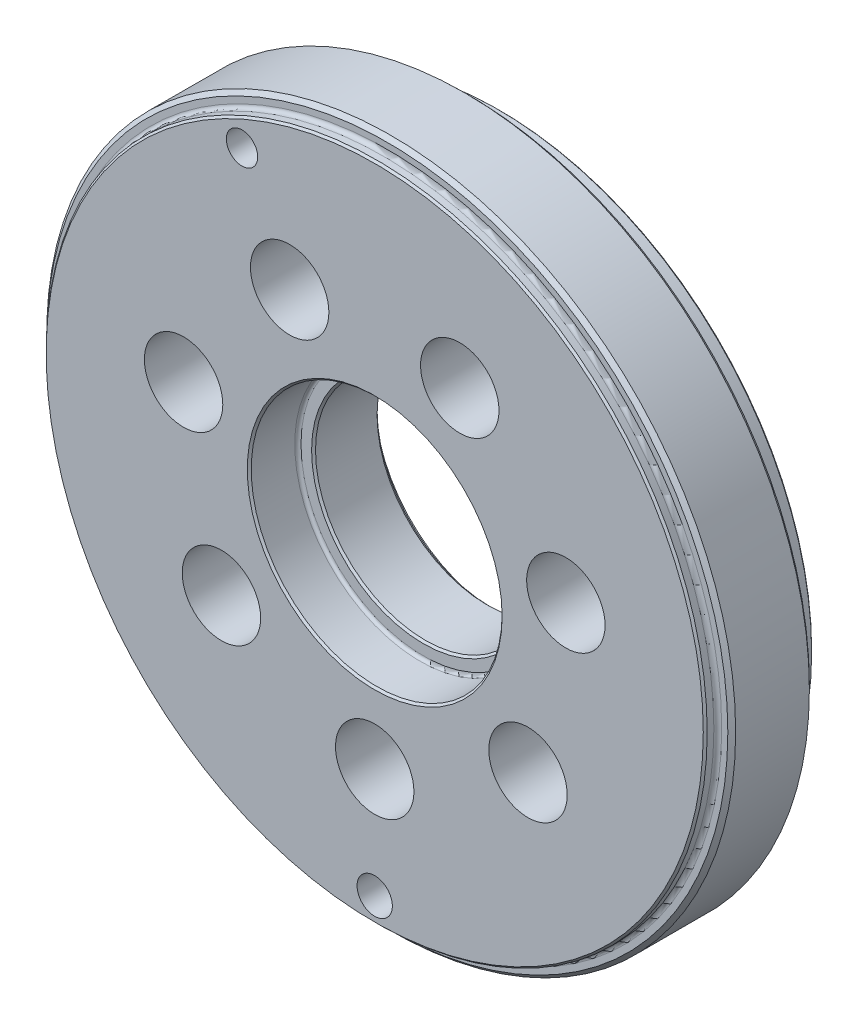
SolidWorks part; units mm, degrees
material "2P Cast Iron"
ref_plane "Front Plane" through (0, 0, 0) normal (0, 0, 1) x (1, 0, 0)
ref_plane "Top Plane" through (0, 0, 0) normal (0, 1, 0) x (1, 0, 0)
ref_plane "Right Plane" through (0, 0, 0) normal (1, 0, 0) x (0, 0, -1)
sketch "Sketch1" plane through (0, 0, 0) normal (0, 0, 1) x (1, 0, 0)
  line L0 (0, 0) -> (86.0326, 0) construction
  line L1 (0, 0) -> (0, 58.9688) construction
  circle A4 centre (0, 0) radius 14
  circle A5 centre (0, 0) radius 43.93
  dimension "D6" = 28
  dimension "D7" = 87.86
extrude "Extrude1" add sketch "Sketch1" against normal blind 16
sketch "Sketch13" plane through (0, 0, 0) normal (1, 0, 0) x (0, 0, -1)
  line L0 (0, 0) -> (24.7077, 0) construction
  line L1 (5.8, 16) -> (0.25, 16)
  line L2 (16, -43.93) -> (16, 43.93) construction
  line L3 (6.2, 15.6) -> (6.2, 14.25)
  line L4 (6.45, 14) -> (14.3, 14)
  line L5 (14.8, 14.5) -> (14.8, 15.6)
  line L6 (15.2, 16) -> (16, 16)
  line L7 (16, 39.72) -> (15.75, 39.97)
  line L9 (0.25, 16) -> (0, 16.25)
  line L10 (14.3, 14) -> (14.8, 14.5)
  line L11 (6.2, 14.25) -> (6.45, 14)
  line L12 (0, 41.9) -> (0.25, 42.15)
  line L13 (0, 43.93) -> (0, -43.93) construction
  line L14 (0, 16.25) -> (0, 41.9)
  line L15 (0.25, 42.15) -> (1.1, 42.15)
  line L16 (1.6, 42.65) -> (1.6, 50.0474)
  line L17 (1.6, 50.0474) -> (-4.8431, 50.0474)
  line L18 (0, 0) -> (19.0487, 0)
  line L19 (16, 16) -> (16, 39.72)
  line L20 (15.75, 39.97) -> (12.4, 39.97)
  line L21 (12, 40.37) -> (12, 50.0474)
  line L22 (12, 50.0474) -> (19.0487, 50.0474)
  line L23 (19.0487, 50.0474) -> (19.0487, 0)
  line L24 (-4.8431, 50.0474) -> (-4.8431, 0)
  line L25 (0, 0) -> (-4.8431, 0)
  arc A0 (5.8, 16) -> (6.2, 15.6) centre (5.8, 15.6) cw
  arc A1 (14.8, 15.6) -> (15.2, 16) centre (15.2, 15.6) cw
  arc A3 (1.1, 42.15) -> (1.6, 42.65) centre (1.1, 42.65) ccw
  arc A4 (12.4, 39.97) -> (12, 40.37) centre (12.4, 40.37) cw
  point P24 (0, 42.15)
  point P39 (16, 39.97)
  dimension "D6" = 0.4
  dimension "D14" = 0.25
  dimension "D18" = 0.4
  dimension "D20" = 0.5
  dimension "D1" = 32
  dimension "D2" = 32
  dimension "D3" = 100.0949
  dimension "D4" = 28
  dimension "D7" = 0.25
  dimension "D8" = 45
  dimension "D9" = 45
  dimension "D10" = 0.5
  dimension "D11" = 1.2
  dimension "D12" = 10.4
  dimension "D13" = 45
  dimension "D15" = 79.94
  dimension "D16" = 84.3
  dimension "D17" = 4
  dimension "D19" = 45
  dimension "D21" = 3.0487
  dimension "D22" = 4.8431
  dimension "D23" = 6.2
  dimension "D24" = 0.25
revolve "Cut-Revolve1" cut sketch "Sketch13" angle 360 about L0
sketch "Sketch9" plane through (0, 0, -16) normal (0, 0, -1) x (-1, 0, 0)
  line L0 (0, 0) -> (34.7, 0) construction
  line L1 (0, 0) -> (0, -40.1442) construction
  line L2 (-3, -23) -> (-3, -27)
  line L3 (3, -27) -> (3, -23)
  circle A0 centre (0, 0) radius 14 construction
  arc A1 (3, -23) -> (-3, -23) centre (0, -23) ccw
  arc A2 (-3, -27) -> (3, -27) centre (0, -27) ccw
  dimension "D1" = 3
  dimension "D2" = 10
  dimension "D3" = 27
  dimension "D4" = 6
extrude "Extrude7" cut sketch "Sketch9" against normal blind 2
sketch "Sketch18" plane through (0, 0, -16) normal (0, 0, -1) x (-1, 0, 0)
  line L0 (0, 0) -> (50.6333, 0) construction
  line L1 (0, 0) -> (0, -49.0418) construction
  line L2 (0, 0) -> (21.5214, -44.6896) construction
  line L3 (9.9793, -20.7223) -> (11.7149, -24.3262) construction
  line L4 (12.6822, -19.4206) -> (14.4178, -23.0245)
  line L5 (7.2764, -22.0239) -> (9.012, -25.6278)
  arc A2 (12.6822, -19.4206) -> (7.2764, -22.0239) centre (9.9793, -20.7223) ccw
  arc A3 (9.012, -25.6278) -> (14.4178, -23.0245) centre (11.7149, -24.3262) ccw
  arc A4 (3, -23) -> (-3, -23) centre (0, -23) ccw construction
  circle A5 centre (0, 0) radius 23 construction
  circle A6 centre (0, 0) radius 27 construction
  point P3 (10.8471, -22.5242)
  dimension "D1" = 25.714
extrude "Cut-Extrude5" cut sketch "Sketch18" against normal blind 0.6
pattern_circular "CirPattern3" count 7 over 360 about axis through (0, 0, 0) along (0, 0, 1) of "Cut-Extrude5"
sketch "Sketch10" plane through (0, 0, -14) normal (0, 0, -1) x (-1, 0, 0)
  line L0 (0, -20) -> (0, -30) construction
  arc A1 (-3, -27) -> (3, -27) centre (0, -27) ccw construction
  circle A2 centre (0, -25) radius 5
  arc A3 (3, -23) -> (-3, -23) centre (0, -23) ccw construction
  dimension "D1" = 10
extrude "Extrude8" cut sketch "Sketch10" against normal up to next
pattern_circular "CirPattern2" count 7 over 360 about axis through (0, 0, 0) along (0, 0, 1) of "Extrude8", "Extrude7"
sketch "Sketch17" plane through (0, 0, 0) normal (0, 0, -1) x (-1, 0, 0)
  line L0 (0, 0) -> (10.8471, 22.5242) construction
  line L1 (0, 0) -> (67.2556, 0) construction
  line L2 (0, 0) -> (0, -48.3478) construction
  circle A0 centre (0, -39) radius 2.25
  circle A1 centre (16.9215, 35.1378) radius 2
  circle A2 centre (0, 0) radius 39 construction
  dimension "D1" = 4.5
  dimension "D2" = 78
  dimension "D3" = 4
hole_wizard "Ø4.0 (4) Diameter Hole1" positions "Sketch22" profile "Sketch21" hole size "Ø4.0" standard "Ansi Metric"
sketch "Sketch22" plane through (0, 0, 0) normal (0, 0, 1) x (1, 0, 0)
  point P0 (-16.9215, 35.1378)
sketch "Sketch21" plane through (-16.9215, 35.1378, 0) normal (1, 0, 0) x (0, -1, 0)
  line L0 (0, 0) -> (0, 7.2017)
  line L1 (0, 7.2017) -> (2, 6)
  line L2 (2, 6) -> (2, 0)
  line L5 (2, 0) -> (0, 0)
  line L10 (0, 7.2017) -> (-2, 6) construction
  line L11 (0, -6.35) -> (0, 107.95) construction
  dimension "Hole Dia." = 4
  dimension "Hole Depth" = 6
  dimension "Drill Angle" = 118
hole_wizard "Ø4.5 (4.5) Diameter Hole2" positions "Sketch24" profile "Sketch23" hole size "Ø4.5" standard "Ansi Metric"
sketch "Sketch24" plane through (0, 0, 0) normal (0, 0, 1) x (1, 0, 0)
  point P0 (0, -39)
sketch "Sketch23" plane through (0, -39, 0) normal (1, 0, 0) x (0, -1, 0)
  line L0 (0, 0) -> (0, 14.8519)
  line L1 (0, 14.8519) -> (2.25, 13.5)
  line L2 (2.25, 13.5) -> (2.25, 0)
  line L5 (2.25, 0) -> (0, 0)
  line L10 (0, 14.8519) -> (-2.25, 13.5) construction
  line L11 (0, -6.35) -> (0, 107.95) construction
  dimension "Hole Dia." = 4.5
  dimension "Hole Depth" = 13.5
  dimension "Drill Angle" = 118
chamfer "Chamfer1" distance 0.5 angle 45 2 edges at (43.93, 0, -1.6) (-43.93, 0, -12)
